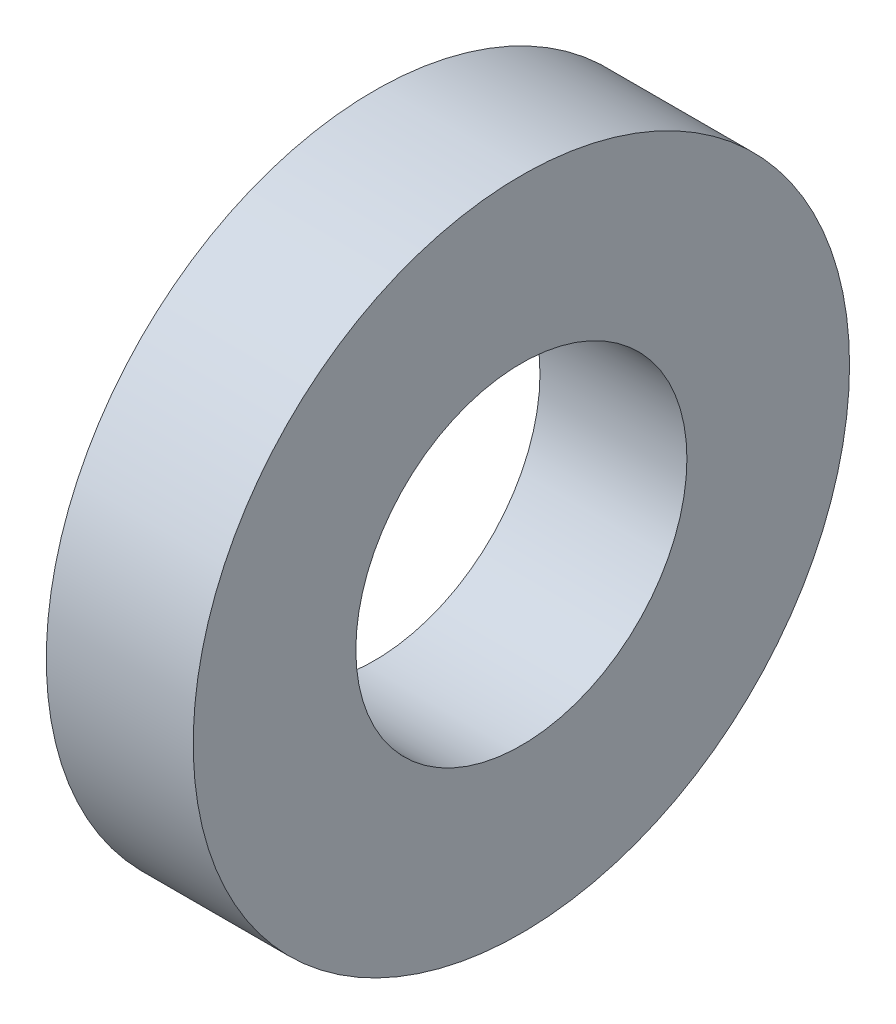
SolidWorks part; units mm, degrees
ref_plane "Front Plane" through (0, 0, 0) normal (0, 0, 1) x (1, 0, 0)
ref_plane "Top Plane" through (0, 0, 0) normal (0, 1, 0) x (1, 0, 0)
ref_plane "Right Plane" through (0, 0, 0) normal (1, 0, 0) x (0, 0, -1)
sketch "Sketch1" plane through (0, 0, 0) normal (1, 0, 0) x (0, 0, -1)
  circle A0 centre (0, 0) radius 33.5
  circle A1 centre (0, 0) radius 16.9
  dimension "D1" = 33.8
  dimension "D2" = 67
extrude "Boss-Extrude1" add sketch "Sketch1" along normal blind 15
